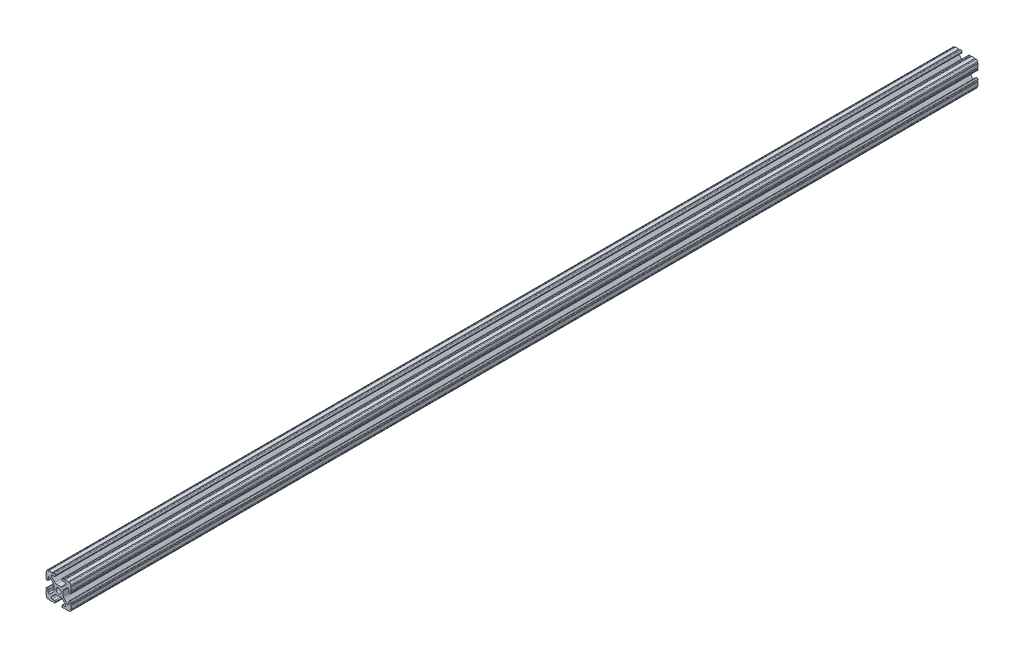
SolidWorks part; units mm, degrees
ref_plane "Front Plane" through (0, 0, 0) normal (0, 0, 1) x (1, 0, 0)
ref_plane "Top Plane" through (0, 0, 0) normal (0, 1, 0) x (1, 0, 0)
ref_plane "Right Plane" through (0, 0, 0) normal (1, 0, 0) x (0, 0, -1)
sketch "Sketch2" plane through (0, 0, 0) normal (0, 0, 1) x (1, 0, 0)
  line L0 (0, 12.7) -> (0, -12.7) construction
  line L1 (-12.7, 0) -> (12.7, 0) construction
  line L2 (3.2512, -12.7) -> (12.7, -12.7)
  line L3 (12.7, -12.7) -> (12.7, -3.2512)
  line L4 (3.2512, -12.7) -> (3.2512, -10.4902)
  line L5 (3.2512, -10.4902) -> (8.9276, -10.4902)
  line L6 (8.9276, -10.4902) -> (3.0856, -4.6482)
  line L7 (0, 0) -> (12.7, -12.7) construction
  line L8 (12.7, -3.2512) -> (10.4902, -3.2512)
  line L9 (10.4902, -3.2512) -> (10.4902, -8.9276)
  line L10 (10.4902, -8.9276) -> (4.6482, -3.0856)
  circle A0 centre (0, 0) radius 2.6035
  arc A1 (6.3485, -10.4902) -> (7.1039, -8.6665) centre (6.3485, -9.4219) ccw construction
  point P8 (0, -4.6482)
  dimension "Center Hole Diameter" = 5.207
  dimension "Rail Height" = 25.4
  dimension "Rail Width" = 25.4
  dimension "T-Slot Width" = 6.5024
  dimension "Slot Inner Width" = 14.8336
  dimension "Thickness" = 2.2098
  dimension "Slot Depth" = 5.842
  dimension "D1" = 2.2098
sketch "Sketch3" plane through (0, 0, 0) normal (1, 0, 0) x (0, 0, -1)
  line L0 (-457.2, -12.7) -> (457.2, -12.7) construction
  line L1 (-431.8, 0) -> (431.8, 0) construction
  dimension "Length" = 914.4
  dimension "D1" = 25.4
sketch "Sketch4" plane through (0, 0, 0) normal (0, 0, 1) x (1, 0, 0)
  line L0 (4.1904, -12.7) -> (10.1173, -12.7)
  line L1 (3.2512, -12.7) -> (12.7, -12.7) construction
  line L2 (3.2512, -12.7) -> (3.2512, -10.4902) construction
  line L3 (3.2512, -10.4902) -> (8.9276, -10.4902) construction
  line L4 (3.2512, -11.4294) -> (3.2512, -11.7608)
  line L5 (4.1904, -10.4902) -> (6.3485, -10.4902)
  line L6 (0, -4.6482) -> (2.164, -4.6482)
  line L7 (8.9276, -10.4902) -> (3.0856, -4.6482) construction
  line L8 (3.7373, -5.2999) -> (7.1039, -8.6665)
  line L9 (12.7, -12.7) -> (12.7, -3.2512) construction
  line L10 (10.4902, -8.9276) -> (4.6482, -3.0856) construction
  line L11 (10.4902, -3.2512) -> (10.4902, -8.9276) construction
  line L12 (10.4902, -6.3485) -> (10.4902, -4.1904)
  line L13 (12.7, -3.2512) -> (10.4902, -3.2512) construction
  line L14 (11.4294, -3.2512) -> (11.7608, -3.2512)
  line L15 (12.7, -4.1904) -> (12.7, -10.1173)
  line L16 (8.6665, -7.1039) -> (5.2999, -3.7373)
  line L17 (4.6482, 0) -> (4.6482, -2.164)
  line L18 (-12.7, 0) -> (12.7, 0) construction
  line L19 (0, -4.6482) -> (0, -2.6035)
  line L20 (0, 12.7) -> (0, -12.7) construction
  line L21 (4.6482, 0) -> (2.6035, 0)
  arc A0 (3.2512, -11.7608) -> (4.1904, -12.7) centre (4.1904, -11.7608) ccw
  arc A2 (3.2512, -11.4294) -> (4.1904, -10.4902) centre (4.1904, -11.4294) cw
  arc A3 (6.3485, -10.4902) -> (7.1039, -8.6665) centre (6.3485, -9.4219) ccw
  arc A4 (2.164, -4.6482) -> (3.7373, -5.2999) centre (2.164, -6.8732) cw
  arc A5 (10.1173, -12.7) -> (12.7, -10.1173) centre (10.1173, -10.1173) ccw
  arc A6 (8.6665, -7.1039) -> (10.4902, -6.3485) centre (9.4219, -6.3485) ccw
  arc A7 (10.4902, -4.1904) -> (11.4294, -3.2512) centre (11.4294, -4.1904) cw
  arc A8 (11.7608, -3.2512) -> (12.7, -4.1904) centre (11.7608, -4.1904) cw
  arc A9 (5.2999, -3.7373) -> (4.6482, -2.164) centre (6.8732, -2.164) cw
  circle A10 centre (0, 0) radius 2.6035 construction
  arc A11 (0, -2.6035) -> (2.6035, 0) centre (0, 0) ccw
  dimension "D1" = 2.5827
  dimension "D2" = 2.225
  dimension "D3" = 0.9392
extrude "Boss-Extrude1" add sketch "Sketch4" along normal mid plane 914.4
sketch "Sketch5" plane through (0, 0, 0) normal (0, 0, 1) x (1, 0, 0)
  line L0 (3.2512, -12.7) -> (12.7, -12.7) construction
  line L1 (4.1904, -10.4902) -> (6.3485, -10.4902) construction
  line L3 (0, 0) -> (12.7, -12.7) construction
  line L4 (6.3485, -10.4902) -> (6.3485, -12.7) construction
  line L5 (8.9276, -10.4902) -> (3.0856, -4.6482) construction
  circle A0 centre (10.3562, -12.7) radius 0.5524
  circle A1 centre (5.796, -12.7) radius 0.5524
  circle A2 centre (12.7, -10.3562) radius 0.5524
  circle A3 centre (12.7, -5.796) radius 0.5524
  point P10 (5.2694, -10.4902)
  point P12 (9.4219, -6.3485)
  dimension "D1" = 1.1049
extrude "Cut-Extrude1" cut sketch "Sketch5" against normal through all both and the other way through all
mirror "Mirror1" about plane through (0, 0, 0) normal (1, 0, 0) of bodies 137 134
mirror "Mirror2" about plane through (0, 0, 0) normal (0, 1, 0) of bodies 135
sketch "Sketch6" plane through (4.6482, 0, 0) normal (1, 0, 0) x (0, 0, -1)
  line L0 (-457.2, -2.164) -> (-457.2, 2.164) construction
  line L2 (-457.2, 0) -> (457.2, 0) construction
  line L3 (457.2, -2.164) -> (457.2, 2.164) construction
  circle A0 centre (-431.8, 0) radius 3
  circle A1 centre (108.2, 0) radius 7590
  dimension "D1" = 6
  dimension "D4" = 15180
  dimension "D2" = 25.4
  dimension "D3" = 540
extrude "Cut-Extrude2" [suppressed] cut sketch "Sketch6" against normal through all both and the other way through all
equation "\"D1@Boss-Extrude1\"=\"Length@Sketch3\""
equation "\"D1@Sketch2\"=\"Thickness@Sketch2\""
equation "\"D2@Sketch4\"=\"Slot Inner Width@Sketch2\"*0.15"
equation "\"D1@Sketch4\"=\"D3@Sketch4\"*2.75"
equation "\"D3@Sketch4\"=\"Thickness@Sketch2\"*0.425"
equation "\"D1@Sketch5\"=\"Thickness@Sketch2\"*0.5"
equation "\"D4@Sketch6\"=600-60mm"
